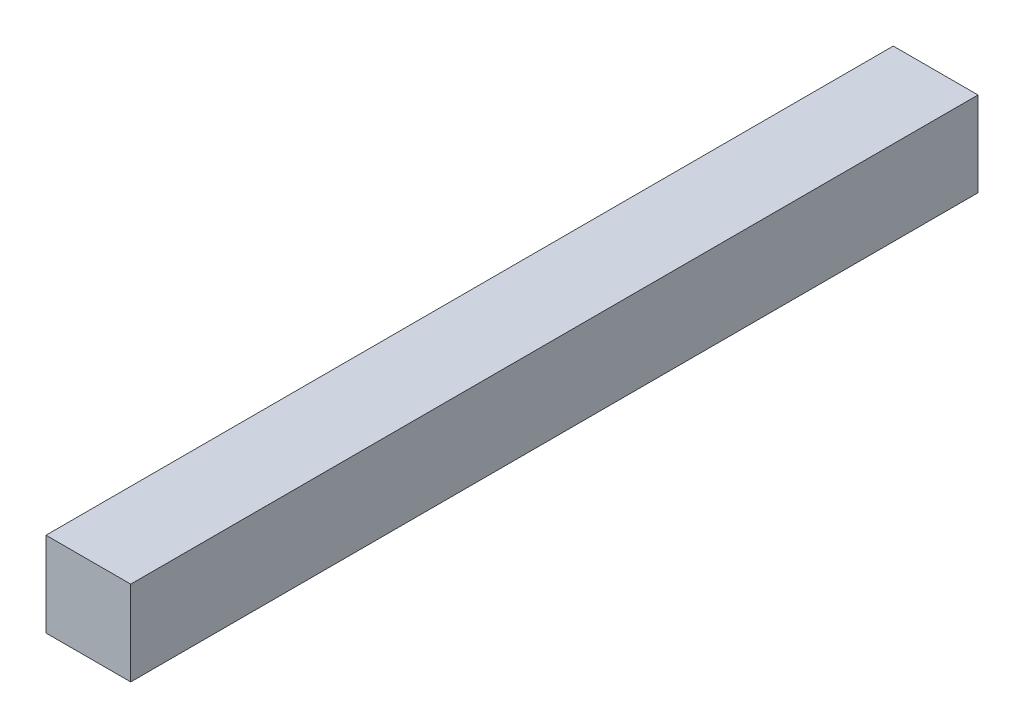
SolidWorks part; units mm, degrees
ref_plane "Front" through (0, 0, 0) normal (0, 0, 1) x (1, 0, 0)
ref_plane "Top" through (0, 0, 0) normal (0, 1, 0) x (1, 0, 0)
ref_plane "Right" through (0, 0, 0) normal (1, 0, 0) x (0, 0, -1)
sketch "草图1" plane through (0, 0, 0) normal (0, 0, 1) x (1, 0, 0)
  line L1 (0, 0) -> (20, 0)
  line L2 (0, 0) -> (0, -20)
  line L3 (0, -20) -> (20, -20)
  line L4 (20, 0) -> (20, -20)
  dimension "D1" = 20
  dimension "D2" = 20
extrude "凸台-拉伸1" add sketch "草图1" along normal blind 200
